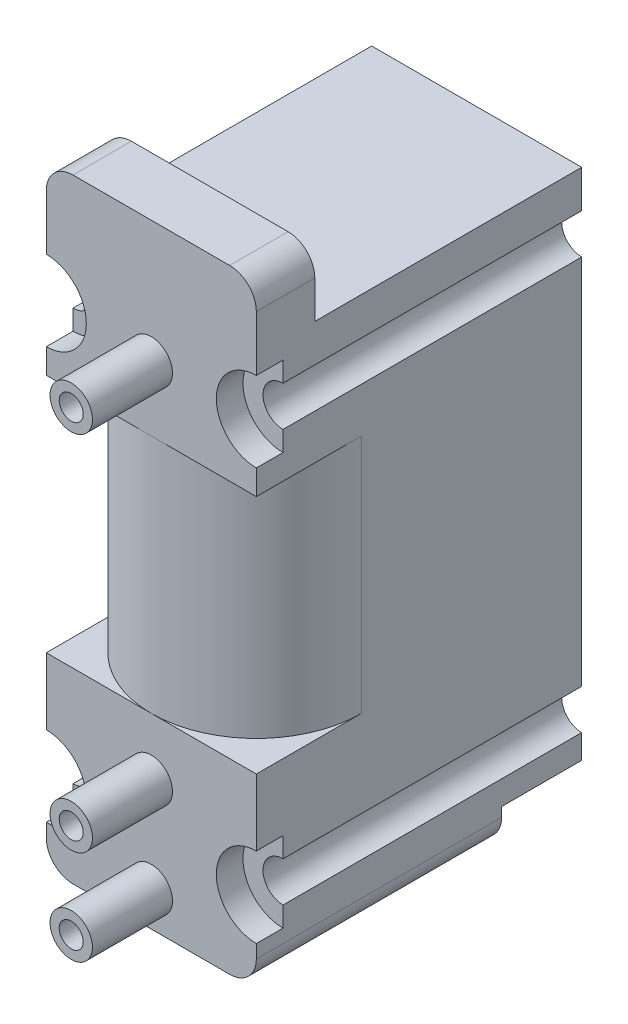
SolidWorks part; units mm, degrees
ref_plane "Front Plane" through (0, 0, 0) normal (0, 0, 1) x (1, 0, 0)
ref_plane "Top Plane" through (0, 0, 0) normal (0, 1, 0) x (1, 0, 0)
ref_plane "Right Plane" through (0, 0, 0) normal (1, 0, 0) x (0, 0, -1)
sketch "Sketch1" plane through (0, 0, 0) normal (0, 0, 1) x (1, 0, 0)
  line L1 (0, 0) -> (7.87, 0)
  line L2 (0, 0) -> (0, 23)
  line L3 (0, 23) -> (7.87, 23)
  line L4 (7.87, 0) -> (7.87, 23)
  dimension "D1" = 7.87
  dimension "D2" = 23
extrude "Boss-Extrude1" add sketch "Sketch1" along normal blind 12.19
sketch "Sketch2" plane through (0, 0, 12.19) normal (0, 0, 1) x (1, 0, 0)
  line L0 (7.87, 23) -> (0, 23) construction
  line L1 (3.935, 23) -> (3.935, 0) construction
  line L2 (0, 0) -> (7.87, 0) construction
  circle A0 centre (3.935, 18.43) radius 0.7938
  circle A1 centre (3.935, 4.8544) radius 0.7938
  circle A2 centre (3.935, 1.31) radius 0.7938
  dimension "D4" = 1.5875
  dimension "D1" = 4.57
  dimension "D2" = 18.1456
  dimension "D3" = 21.69
extrude "Boss-Extrude2" add sketch "Sketch2" along normal blind 3
sketch "Sketch3" plane through (0, 0, 12.19) normal (0, 0, 1) x (1, 0, 0)
  line L0 (0, 23) -> (0, 0) construction
  line L1 (0, 18.43) -> (3.935, 18.43) construction
  line L2 (3.935, 18.43) -> (3.935, 4.8544) construction
  circle A0 centre (0, 18.43) radius 0.75
  circle A1 centre (0, 3) radius 0.75
  circle A7 centre (7.87, 3) radius 0.75
  circle A8 centre (7.87, 18.43) radius 0.75
  dimension "D1" = 1.5
  dimension "D2" = 3
extrude "Cut-Extrude1" cut sketch "Sketch3" against normal up to surface (12.19 mm away) contours A8 | A7 | A0 | A1 up to face at (3.935, 11.5, 0)
fillet "Fillet1" radius 1 4 edges at (7.87, 23, 6.095) (0, 23, 6.095) (0, 0, 6.095) (7.87, 0, 6.095)
sketch "Sketch4" plane through (0, 0, 12.19) normal (0, 0, 1) x (1, 0, 0)
  line L0 (3.935, 18.43) -> (3.935, 4.8544) construction
  circle A0 centre (0, 18.43) radius 1.5
  circle A1 centre (0, 3) radius 1.5
  circle A2 centre (7.87, 3) radius 1.5
  circle A3 centre (7.87, 18.43) radius 1.5
  dimension "D1" = 3
extrude "Cut-Extrude2" cut sketch "Sketch4" against normal blind 1
sketch "Sketch5" plane through (0, 0, 0) normal (0, 0, -1) x (-1, 0, 0)
  line L0 (-7.87, 19.18) -> (-7.87, 22) construction
  line L1 (-7.87, 20.59) -> (0, 20.59)
  line L2 (-7.87, 20.59) -> (-7.87, 23)
  line L3 (-7.87, 23) -> (0, 23)
  line L4 (0, 20.59) -> (0, 23)
  line L5 (-6.87, 23) -> (-1, 23) construction
  line L6 (0, 22) -> (0, 19.18) construction
extrude "Cut-Extrude3" cut sketch "Sketch5" against normal blind 10
sketch "Sketch6" plane through (0, 0, 0) normal (0, 0, -1) x (-1, 0, 0)
  line L0 (-3.935, 2.4689) -> (-3.935, 0) construction
  line L2 (-1, 0) -> (-6.87, 0) construction
  line L3 (-7.87, 1.3491) -> (-7.0138, 1.3491)
  line L4 (-7.87, 1) -> (-7.87, 2.25) construction
  line L5 (-6.5138, 1.8491) -> (-6.5138, 1.9689)
  line L6 (-6.0138, 2.4689) -> (-1.8562, 2.4689)
  line L7 (-1, 0) -> (-6.87, 0)
  line L8 (-7.87, 1) -> (-7.87, 1.3491)
  line L9 (0, 1) -> (0, 1.3491)
  line L10 (-1.3562, 1.8491) -> (-1.3562, 1.9689)
  line L11 (0, 1.3491) -> (-0.8562, 1.3491)
  arc A0 (-7.0138, 1.3491) -> (-6.5138, 1.8491) centre (-7.0138, 1.8491) ccw
  arc A1 (-6.5138, 1.9689) -> (-6.0138, 2.4689) centre (-6.0138, 1.9689) cw
  arc A2 (-7.87, 1) -> (-6.87, 0) centre (-6.87, 1) ccw construction
  arc A3 (-7.87, 1) -> (-6.87, 0) centre (-6.87, 1) ccw
  arc A4 (0, 1) -> (-1, 0) centre (-1, 1) cw
  arc A5 (-1.3562, 1.9689) -> (-1.8562, 2.4689) centre (-1.8562, 1.9689) ccw
  arc A6 (-0.8562, 1.3491) -> (-1.3562, 1.8491) centre (-0.8562, 1.8491) cw
  dimension "D1" = 0.5
  dimension "D3" = 0.9009
  dimension "D4" = 0.8562
  dimension "D2" = 2.4689
extrude "Cut-Extrude4" cut sketch "Sketch6" against normal blind 3
sketch "Sketch7" plane through (0, 0, 15.19) normal (0, 0, 1) x (1, 0, 0)
  circle A0 centre (3.935, 18.43) radius 0.45
  circle A1 centre (3.935, 4.8544) radius 0.45
  circle A2 centre (3.935, 1.31) radius 0.45
  dimension "D1" = 0.9
extrude "Cut-Extrude5" cut sketch "Sketch7" against normal blind 8
ref_plane "Plane1" through (0, 7, 0) normal (0, -1, 0) x (-1, 0, 0)
sketch "Sketch8" plane through (0, 7, 0) normal (0, -1, 0) x (-1, 0, 0)
  line L28 (0, -3) -> (0, -12.19) construction
  line L29 (-1, -12.19) -> (0, -12.19) construction
  line L30 (-7.87, -12.19) -> (-7.87, -3) construction
  line L31 (0, -8.255) -> (0, -12.19)
  line L32 (0, -12.19) -> (-7.87, -12.19)
  line L33 (-7.87, -12.19) -> (-7.87, -8.255)
  arc A0 (-7.87, -8.255) -> (0, -8.255) centre (-3.935, -8.255) ccw
extrude "Cut-Extrude6" cut sketch "Sketch8" against normal blind 9 contours A0 L32 L31 | A0 L33 L32
